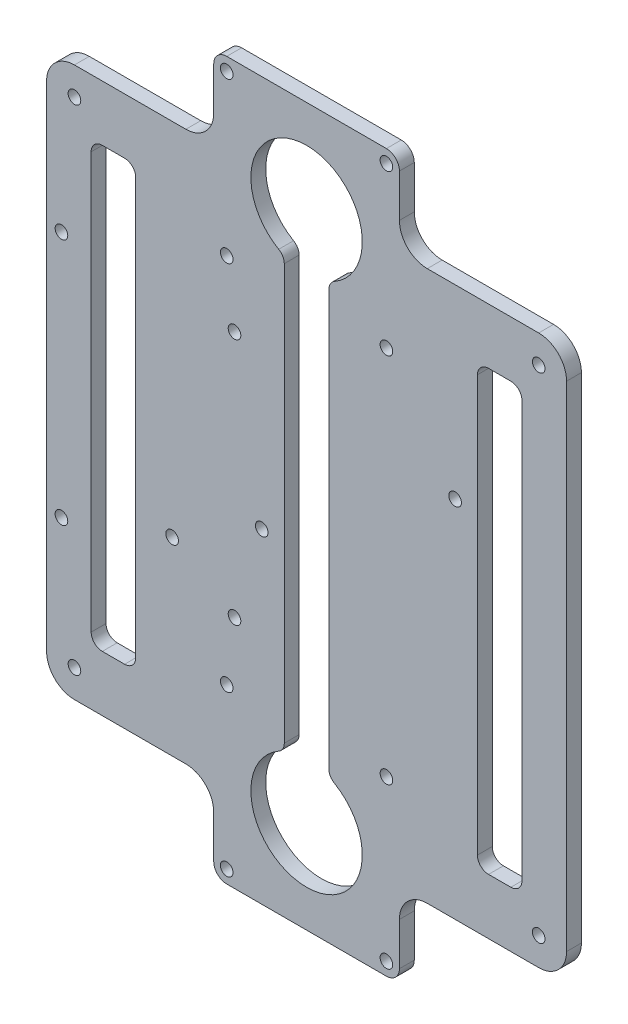
SolidWorks part; units mm, degrees
material "MDF"
ref_plane "正面" through (0, 0, 0) normal (1, 0, 0) x (0, 1, 0)
ref_plane "平面" through (0, 0, 0) normal (0, 0, 1) x (0, 1, 0)
ref_plane "右側面" through (0, 0, 0) normal (0, 1, 0) x (-1, 0, 0)
sketch "ｽｹｯﾁ1" plane through (0, 0, 0) normal (0, 0, 1) x (0, 1, 0)
  line L1 (0, 0) -> (148, 0)
  line L2 (0, 0) -> (0, 45)
  line L3 (0, 140) -> (148, 140)
  line L4 (148, 0) -> (148, 45)
  line L7 (74, 140) -> (74, 0) construction
  line L13 (0, 95) -> (-22.5, 95)
  line L14 (-22.5, 95) -> (-22.5, 45)
  line L15 (-22.5, 45) -> (0, 45)
  line L16 (170.5, 45) -> (148, 45)
  line L17 (170.5, 95) -> (170.5, 45)
  line L18 (148, 95) -> (170.5, 95)
  line L19 (0, 95) -> (0, 140)
  line L20 (148, 95) -> (148, 140)
  circle A0 centre (2.5, 70) radius 15
  circle A1 centre (145.5, 70) radius 15
  point P18 (-22.5, 70)
  point P21 (0, 0)
  dimension "D6" = 30
  dimension "D1" = 140
  dimension "D2" = 148
  dimension "D3" = 22.5
  dimension "D4" = 50
  dimension "D5" = 45
  dimension "D7" = 25
extrude "ﾎﾞｽ - 押し出し1" add sketch "ｽｹｯﾁ1" along normal blind 4
sketch "ｽｹｯﾁ2" plane through (0, 0, 4) normal (0, 0, 1) x (1, 0, 0)
  line L0 (0, 74) -> (-140, 74) construction
  line L1 (0, 0) -> (0, 148) construction
  line L2 (-140, 148) -> (-140, 0) construction
  line L3 (0, 148) -> (-45, 148) construction
  line L5 (-136, 107.3) -> (-89.4, 107.3) construction
  line L6 (-136, 107.3) -> (-136, 40.7) construction
  line L7 (-136, 40.7) -> (-89.4, 40.7) construction
  line L8 (-89.4, 107.3) -> (-89.4, 40.7) construction
  line L10 (-91.5, 24) -> (-48.5, 24) construction
  line L11 (-91.5, 24) -> (-91.5, -19) construction
  line L12 (-91.5, -19) -> (-48.5, -19) construction
  line L13 (-48.5, 24) -> (-48.5, -19) construction
  line L17 (0, 148) -> (-45, 148) construction
  line L21 (-95, -22.5) -> (-45, -22.5) construction
  circle A0 centre (-70, 2.5) radius 15 construction
  circle A1 centre (-70, 2.5) radius 15 construction
  point P0 (-132.5, 140.5)
  point P1 (-7.5, 140.5)
  point P10 (-106.2, 51.02)
  point P11 (-30, 98.01)
  point P12 (-7.5, 7.5)
  point P13 (-132.5, 7.5)
  point P15 (-82.07, 64.99)
  point P21 (-136, 107.3)
  point P22 (-89.4, 107.3)
  point P23 (-89.4, 40.7)
  point P24 (-136, 40.7)
  point P233 (-91.5, 24)
  point P236 (-48.5, 24)
  point P239 (-48.5, -19)
  point P242 (-91.5, -19)
  point P257 (0, 0)
  point P258 (0, 0)
  point P259 (0, 0)
  point P260 (0, 0)
  point P261 (0, 0)
  point P264 (-70, -22.5)
  point P265 (-70, -19)
  point P270 (-91.5, 167)
  point P271 (-48.5, 167)
  point P272 (-48.5, 124)
  point P273 (-91.5, 124)
  point P278 (-91.5, 2.5)
  point P279 (0, 0)
  dimension "D1" = 7.5
  dimension "D2" = 7.5
  dimension "D3" = 7.5
  dimension "D4" = 76.2
  dimension "D5" = 46.99
  dimension "D8" = 52.07
  dimension "D9" = 33.02
  dimension "D10" = 30
  dimension "D11" = 9.01
  dimension "D12" = 46.6
  dimension "D13" = 66.6
  dimension "D14" = 33.3
  dimension "D15" = 4
  dimension "D16" = 43
  dimension "D17" = 43
  dimension "D18" = 74
hole_wizard "M3 すきま穴1" positions "ｽｹｯﾁ2" profile "ｽｹｯﾁ3" hole size "M3" standard "JIS" end condition through all
sketch "ｽｹｯﾁ3" plane through (-132.5, 140.5, 4) normal (1, 0, 0) x (0, -1, 0)
  line L0 (0, 0) -> (0, 4)
  line L1 (0, 4) -> (1.7, 4)
  line L2 (1.7, 4) -> (1.7, 0)
  line L5 (1.7, 0) -> (0, 0)
  line L11 (0, -6.35) -> (0, 107.95) construction
  dimension "通し穴の直径" = 3.4
  dimension "通し穴の深さ" = 4
fillet "ﾌｨﾚｯﾄ7" radius 7.5 8 edges at (0, 0, 2) (0, 148, 2) (-140, 148, 2) (-45, 148, 2) (-45, 0, 2) (-140, 0, 2) (-95, 148, 2) (-95, 0, 2)
fillet "ﾌｨﾚｯﾄ8" radius 3.5 4 edges at (-95, 170.5, 2) (-45, 170.5, 2) (-45, -22.5, 2) (-95, -22.5, 2)
sketch "ｽｹｯﾁ4" plane through (0, 0, 4) normal (0, 0, 1) x (1, 0, 0)
  line L0 (-70, 145.5) -> (-70, 2.5) construction
  line L1 (-128, 15) -> (-116, 15)
  line L2 (-128, 15) -> (-128, 133)
  line L3 (-128, 133) -> (-116, 133)
  line L4 (-116, 15) -> (-116, 133)
  line L5 (-128, 15) -> (-116, 133) construction
  line L6 (-128, 133) -> (-116, 15) construction
  line L7 (-64, 145.5) -> (-64, 2.5)
  line L8 (-76, 145.5) -> (-76, 2.5)
  line L9 (-140, 140.5) -> (-140, 7.5) construction
  line L10 (-70, -22.5) -> (-70, -12.5) construction
  line L11 (-91.5, -22.5) -> (-48.5, -22.5) construction
  line L12 (-12, 133) -> (-24, 133)
  line L13 (-24, 15) -> (-24, 133)
  line L14 (-12, 15) -> (-24, 15)
  line L15 (-12, 15) -> (-12, 133)
  arc A0 (-64, 145.5) -> (-76, 145.5) centre (-70, 145.5) ccw
  arc A1 (-76, 2.5) -> (-64, 2.5) centre (-70, 2.5) ccw
  circle A2 centre (-70, 2.5) radius 15 construction
  point P4 (-122, 74)
  point P9 (-70, 74)
  point P17 (-140, 74)
  dimension "D1" = 118
  dimension "D2" = 12
  dimension "D3" = 12
  dimension "D4" = 12
extrude "ｶｯﾄ - 押し出し1" cut sketch "ｽｹｯﾁ4" against normal through all
fillet "ﾌｨﾚｯﾄ9" radius 3 12 edges at (-24, 15, 2) (-12, 15, 2) (-12, 133, 2) (-24, 133, 2) (-64, 131.7523, 2) (-76, 131.7523, 2) (-64, 16.2477, 2) (-76, 16.2477, 2) (-128, 133, 2) (-116, 133, 2) (-116, 15, 2) (-128, 15, 2)
